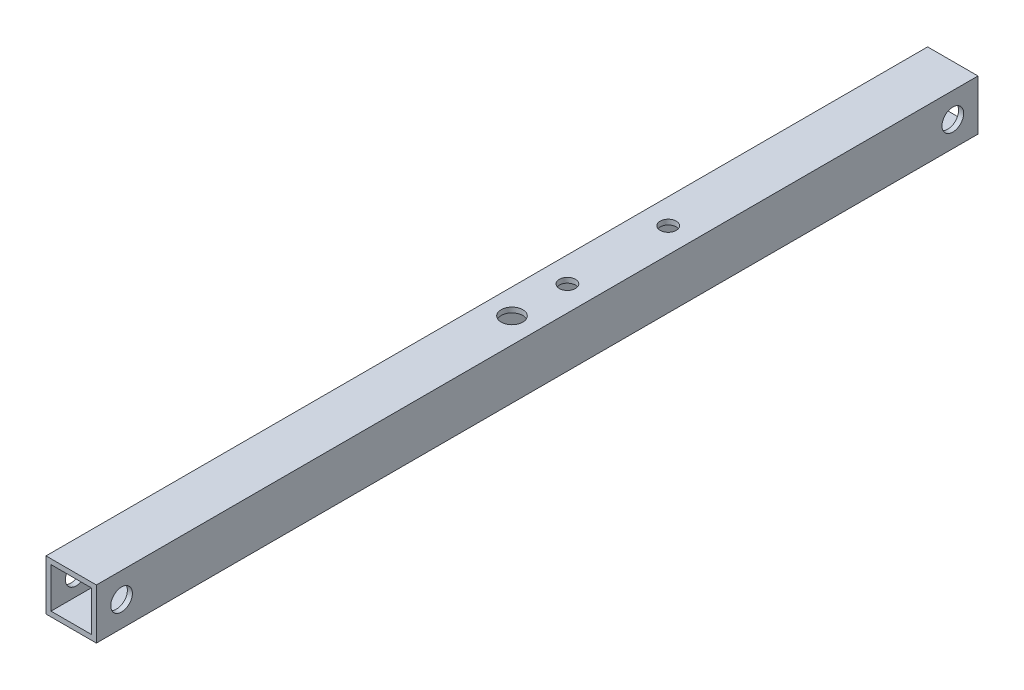
SolidWorks part; units mm, degrees
material "5052-H34"
ref_plane "正面" through (0, 0, 0) normal (0, 0, 1) x (1, 0, 0)
ref_plane "平面" through (0, 0, 0) normal (0, 1, 0) x (1, 0, 0)
ref_plane "右側面" through (0, 0, 0) normal (1, 0, 0) x (0, 0, -1)
sketch "ｽｹｯﾁ1" plane through (0, 0, 0) normal (0, 0, 1) x (1, 0, 0)
  line L1 (5, 5) -> (-5, 5)
  line L2 (5, 5) -> (5, -5)
  line L3 (5, -5) -> (-5, -5)
  line L4 (-5, 5) -> (-5, -5)
  line L5 (5, 5) -> (-5, -5) construction
  line L6 (5, -5) -> (-5, 5) construction
  point P0 (0, 0)
  dimension "D1" = 10
  dimension "D2" = 10
extrude "押し出し-薄板1" add sketch "ｽｹｯﾁ1" along normal blind 175 thin thin type one direction reverse wall 1
sketch "ｽｹｯﾁ2" plane through (5, 0, 0) normal (1, 0, 0) x (0, 0, -1)
  line L0 (-175, 0) -> (0, 0) construction
  line L1 (-175, -5) -> (-175, 5) construction
  line L2 (-87.5, 0) -> (-87.5, 5) construction
  line L3 (-175, 5) -> (0, 5) construction
  circle A0 centre (-170, 0) radius 2.15
  circle A1 centre (-5, 0) radius 2.15
  dimension "D1" = 4.3
  dimension "D2" = 5
extrude "ｶｯﾄ - 押し出し1" cut sketch "ｽｹｯﾁ2" against normal through all
sketch "ｽｹｯﾁ3" plane through (0, 5, 0) normal (0, 1, 0) x (1, 0, 0)
  line L0 (0, 0) -> (0, -175) construction
  line L1 (5, -175) -> (-5, -175) construction
  line L2 (0, -87.5) -> (5, -87.5) construction
  line L3 (5, -175) -> (5, 0) construction
  circle A0 centre (0, -76.5) radius 1.6
  circle A1 centre (0, -56.5) radius 1.6
  circle A2 centre (0, -87.5) radius 2.15
  dimension "D1" = 3.2
  dimension "D2" = 11
  dimension "D3" = 3.2
  dimension "D4" = 20
  dimension "D5" = 4.3
extrude "ｶｯﾄ - 押し出し2" cut sketch "ｽｹｯﾁ3" against normal through all
sketch "ｽｹｯﾁ4" plane through (0, -5, 0) normal (0, -1, 0) x (1, 0, 0)
  circle A0 centre (0, 87.5) radius 4
  dimension "D1" = 8
extrude "ｶｯﾄ - 押し出し3" cut sketch "ｽｹｯﾁ4" against normal up to surface (9 mm away) up to face at (2.15, 4, 87.5)
